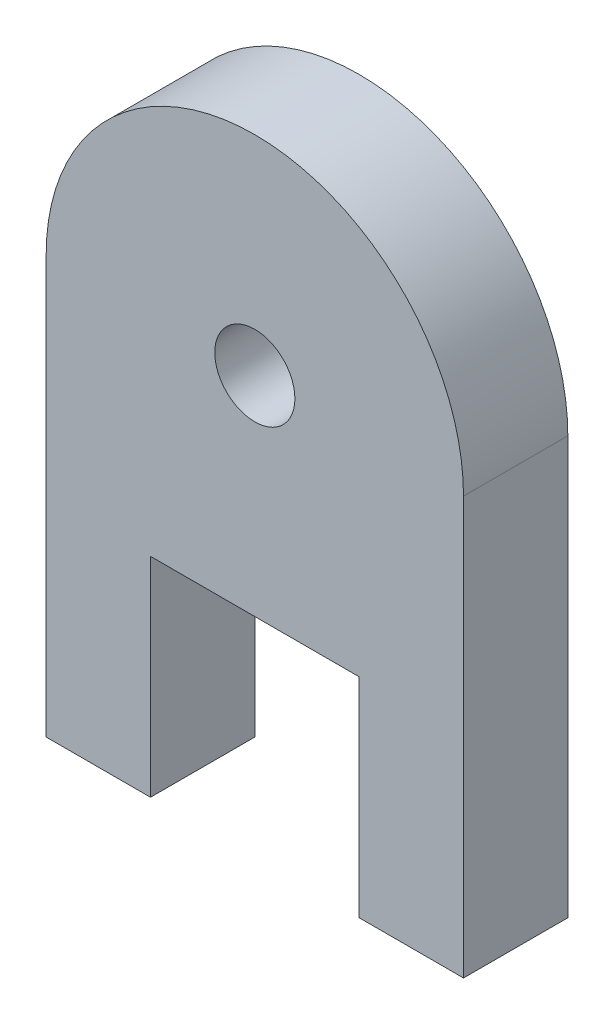
SolidWorks part; units mm, degrees
material "Delrin 2700 NC010, Low Viscosity Acetal Copolymer (SS)"
ref_plane "Front Plane" through (0, 0, 0) normal (0, 0, 1) x (1, 0, 0)
ref_plane "Top Plane" through (0, 0, 0) normal (0, 1, 0) x (1, 0, 0)
ref_plane "Right Plane" through (0, 0, 0) normal (1, 0, 0) x (0, 0, -1)
sketch "Sketch1" plane through (0, 0, 0) normal (0, 0, 1) x (1, 0, 0)
  line L0 (-3.175, 0) -> (0, 0) construction
  line L1 (0, 0) -> (3.175, 0) construction
  line L2 (-3.175, 0) -> (-3.175, -6.35)
  line L3 (-3.175, -6.35) -> (3.175, -6.35)
  line L4 (3.175, -6.35) -> (3.175, 0)
  circle A0 centre (0, 0) radius 0.6096
  arc A1 (-3.175, 0) -> (3.175, 0) centre (0, 0) cw
  dimension "D1" = 1.2192
  dimension "D2" = 6.35
  dimension "D3" = 6.35
extrude "Boss-Extrude1" add sketch "Sketch1" along normal blind 1.5875
sketch "Sketch2" plane through (0, 0, 0) normal (0, 0, -1) x (-1, 0, 0)
  line L0 (3.175, -6.35) -> (-3.175, -6.35) construction
  line L1 (-1.5875, -6.35) -> (1.5875, -6.35)
  line L2 (-1.5875, -6.35) -> (-1.5875, -3.175)
  line L3 (-1.5875, -3.175) -> (1.5875, -3.175)
  line L4 (1.5875, -6.35) -> (1.5875, -3.175)
  line L5 (-1.5875, -6.35) -> (-3.175, -6.35) construction
  line L6 (1.5875, -6.35) -> (3.175, -6.35) construction
  dimension "D1" = 3.175
  dimension "D2" = 1.5875
extrude "Cut-Extrude1" cut sketch "Sketch2" against normal through all
